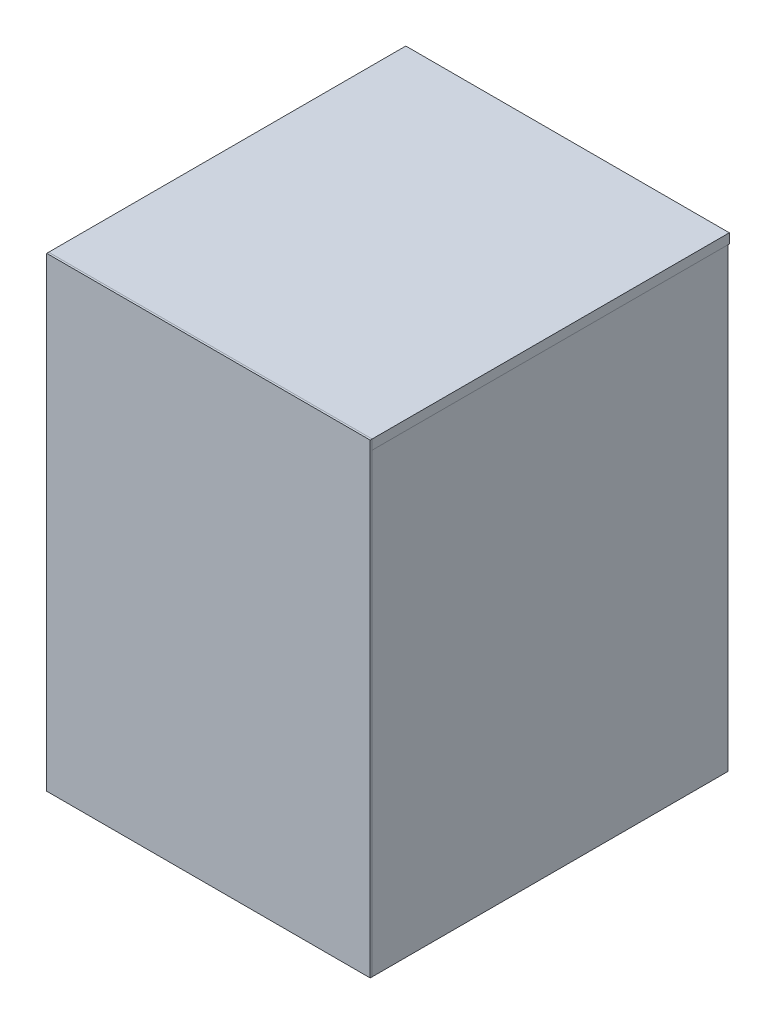
SolidWorks part; units mm, degrees
ref_plane "Front" through (0, 0, 0) normal (0, 0, 1) x (1, 0, 0)
ref_plane "Top" through (0, 0, 0) normal (0, 1, 0) x (1, 0, 0)
ref_plane "Right" through (0, 0, 0) normal (1, 0, 0) x (0, 0, -1)
sketch "Sketch1" plane through (0, 0, 0) normal (0, 0, 1) x (1, 0, 0)
  line L0 (0, 0) -> (0, 690) construction
  line L1 (-250, 690) -> (-235, 690)
  line L2 (-250, 690) -> (-250, -15)
  line L3 (-250, -15) -> (-235, -15)
  line L4 (-235, 690) -> (-235, -15)
  line L5 (235, 690) -> (235, -15)
  line L6 (250, -15) -> (235, -15)
  line L7 (250, 690) -> (250, -15)
  line L8 (250, 690) -> (235, 690)
  dimension "D1" = 15
  dimension "D2" = 470
  dimension "D3" = 15
  dimension "D4" = 690
extrude "Boss-Extrude1" add sketch "Sketch1" along normal blind 550
sketch "Sketch2" plane through (0, 0, 0) normal (0, 0, 1) x (1, 0, 0)
  line L0 (235, 690) -> (235, -15) construction
  line L1 (-235, -15) -> (235, -15)
  line L2 (-235, -15) -> (-235, 0)
  line L3 (-235, 0) -> (235, 0)
  line L4 (235, -15) -> (235, 0)
  line L5 (-250, -15) -> (-235, -15) construction
extrude "Boss-Extrude2" add sketch "Sketch2" along normal offset from surface (515 mm away) 15 from offset 20 separate body up to face at (-242.5, 337.5, 550)
sketch "Sketch3" plane through (0, 0, 0) normal (0, 0, 1) x (1, 0, 0)
  line L0 (250, -15) -> (250, 690) construction
  line L1 (-250, 690) -> (250, 690)
  line L2 (-250, 690) -> (-250, 705)
  line L3 (-250, 705) -> (250, 705)
  line L4 (250, 690) -> (250, 705)
  line L5 (-250, -15) -> (-235, -15) construction
extrude "Boss-Extrude3" add sketch "Sketch3" along normal up to surface (552 mm away) from offset 2 separate body up to face at (-242.5, 337.5, 550) offset against normal yes
sketch "Sketch4" plane through (0, 0, 20) normal (0, 0, -1) x (-1, 0, 0)
  line L0 (-235, 690) -> (-235, -15) construction
  line L1 (-235, 600) -> (235, 600)
  line L2 (-235, 600) -> (-235, 585)
  line L3 (-235, 585) -> (235, 585)
  line L4 (235, 600) -> (235, 585)
  line L5 (235, -15) -> (235, 690) construction
  line L6 (235, 0) -> (235, -15) construction
  line L7 (250, 690) -> (-250, 690) construction
  dimension "D1" = 105
extrude "Boss-Extrude4" add sketch "Sketch4" against normal blind 50
sketch "Sketch5" plane through (0, 0, 0) normal (1, 0, 0) x (0, 0, -1)
  line L0 (-550, 690) -> (0, 690) construction
  line L1 (-550, 690) -> (-535, 690)
  line L2 (-550, 690) -> (-550, 640)
  line L3 (-550, 640) -> (-535, 640)
  line L4 (-535, 690) -> (-535, 640)
  line L5 (-70, 585) -> (-85, 585)
  line L6 (-70, 585) -> (-70, 690)
  line L7 (-70, 690) -> (-85, 690)
  line L8 (-85, 585) -> (-85, 690)
  line L9 (-20, 600) -> (-20, 585) construction
  dimension "D1" = 50
extrude "Boss-Extrude5" add sketch "Sketch5" along normal up to next and the other way up to next separate body
sketch "Sketch7" plane through (0, 0, 550) normal (0, 0, 1) x (1, 0, 0)
  line L1 (-250, 705) -> (250, 705)
  line L2 (-250, 705) -> (-250, -15)
  line L3 (-250, -15) -> (250, -15)
  line L4 (250, 705) -> (250, -15)
extrude "Boss-Extrude6" add sketch "Sketch7" along normal blind 3 separate body
sketch "Sketch10" plane through (0, 0, 70) normal (0, 0, -1) x (-1, 0, 0)
  line L0 (-40, 645) -> (40, 645) construction
  line L1 (-40, 682.5) -> (40, 682.5)
  line L2 (-40, 607.5) -> (40, 607.5)
  line L3 (-235, 690) -> (-235, 600) construction
  arc A0 (-40, 682.5) -> (-40, 607.5) centre (-40, 645) ccw
  arc A1 (40, 607.5) -> (40, 682.5) centre (40, 645) ccw
  point P2 (0, 645)
  point P7 (-235, 645)
  point P13 (0, 607.5)
  dimension "D1" = 80
  dimension "D2" = 75
extrude "Cut-Extrude2" cut sketch "Sketch10" against normal up to next (15 mm away)
sketch "Sketch8" plane through (0, 0, 0) normal (0, 1, 0) x (1, 0, 0)
  line L2 (235, -30) -> (235, -20)
  line L3 (235, -535) -> (235, -20) construction
  line L4 (235, -20) -> (220, -20)
  line L5 (235, -20) -> (-235, -20) construction
  dimension "D1" = 15
  dimension "D2" = 10
extrude "Alu-profiles" add sketch "Sketch8" along normal up to surface (585 mm away) separate body thin up to face at (0, 585, 45) thin type one direction reverse wall 2
mirror "Mirror2" about plane through (0, 0, 0) normal (1, 0, 0) of bodies 109
sketch "Sketch9" plane through (0, 0, 20) normal (0, 0, -1) x (-1, 0, 0)
  line L0 (0, 705) -> (0, 292.5) construction
  line L2 (0, 292.5) -> (-220, 292.5) construction
  line L5 (-250, 705) -> (250, 705) construction
  line L6 (-220, 585) -> (-220, 0) construction
  circle A0 centre (-225, 517.5) radius 2.5
  circle A1 centre (-225, 67.5) radius 2.5
  circle A2 centre (225, 67.5) radius 2.5
  circle A3 centre (225, 517.5) radius 2.5
  point P4 (0, 301.6856)
  point P5 (0, 705)
  point P16 (-220, 292.5)
  dimension "D1" = 5
  dimension "D2" = 450
  dimension "D3" = 450
extrude "Cut-Extrude1" cut sketch "Sketch9" against normal up to next (2 mm away)
